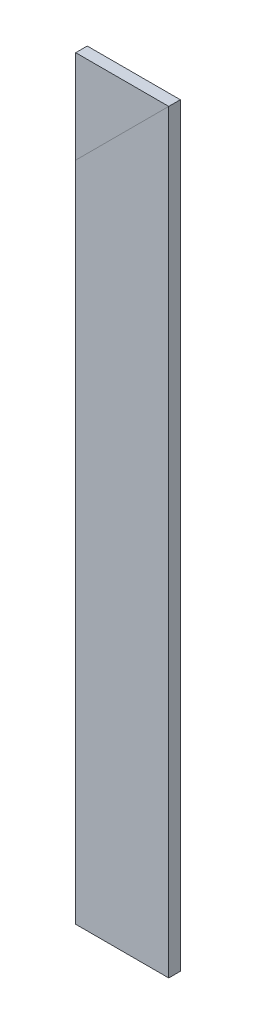
SolidWorks part; units mm, degrees
ref_plane "Alzado" through (0, 0, 0) normal (0, 0, 1) x (1, 0, 0)
ref_plane "Planta" through (0, 0, 0) normal (0, 1, 0) x (1, 0, 0)
ref_plane "Vista lateral" through (0, 0, 0) normal (1, 0, 0) x (0, 0, -1)
sketch "Croquis2" plane through (0, 0, 0) normal (1, 0, 0) x (0, 0, -1)
  line L1 (-3.155, 25.4) -> (3.155, 25.4)
  line L2 (-3.155, 25.4) -> (-3.155, -25.4)
  line L3 (-3.155, -25.4) -> (3.155, -25.4)
  line L4 (3.155, 25.4) -> (3.155, -25.4)
  line L5 (-3.155, 25.4) -> (3.155, -25.4) construction
  line L6 (-3.155, -25.4) -> (3.155, 25.4) construction
  point P0 (0, 0)
  dimension "D1" = 50.8
  dimension "D2" = 6.31
sketch3d "Croquis3D1"
  line L0 (0, 0, 0) -> (171, 0, 0)
  line L1 (171, 0, 0) -> (171, 0, -60)
  line L2 (171, 0, -60) -> (480, 0, -60)
  line L3 (480, 0, -60) -> (480, -386.69, -60)
  dimension "D1" = 171
  dimension "D2" = 60
  dimension "D3" = 309
  dimension "D4" = 386.69
sweep "Barrer1" add profiles "Croquis2" path "Croquis3D1"
sketch "Croquis3" plane through (0, -25.4, 0) normal (0, -1, 0) x (1, 0, 0)
  line L0 (0, 3.155) -> (0, -3.155)
  line L1 (0, 3.155) -> (0, -3.155) construction
  line L2 (0, 3.155) -> (0, -3.155) construction
  line L3 (0, -3.155) -> (174.155, -3.155)
  line L4 (174.155, 3.155) -> (174.155, -56.845) construction
  line L5 (174.155, -3.155) -> (174.155, 3.155)
  line L6 (174.155, 3.155) -> (0, 3.155)
extrude "Cortar-Extruir1" cut sketch "Croquis3" against normal blind 70
sketch "Croquis4" plane through (0, 0, -56.845) normal (0, 0, 1) x (1, 0, 0)
  line L0 (454.6, -386.69) -> (454.6, -335.89)
  line L1 (454.6, -25.4) -> (454.6, -386.69) construction
  line L2 (454.6, -335.89) -> (460.91, -335.89)
  line L3 (460.91, -335.89) -> (460.91, -386.69)
  line L4 (505.4, -386.69) -> (454.6, -386.69) construction
  line L5 (460.91, -386.69) -> (454.6, -386.69)
  dimension "D1" = 50.8
  dimension "D2" = 6.31
extrude "Saliente-Extruir1" add sketch "Croquis4" along normal blind 40
sketch "Croquis5" plane through (460.91, 0, 0) normal (1, 0, 0) x (0, 0, -1)
  line L0 (27.805, -378.6) -> (34.155, -378.6) construction
  line L1 (34.155, -346.6) -> (39.5306, -349.9802) construction
  circle A0 centre (34.155, -378.6) radius 6.35 construction
  circle A1 centre (34.155, -346.6) radius 6.35 construction
  circle A2 centre (34.155, -346.6) radius 6.35
  circle A3 centre (34.155, -378.6) radius 6.35
extrude "Cortar-Extruir2" cut sketch "Croquis5" against normal blind 10
sketch "Croquis6" plane through (167.845, 0, 0) normal (-1, 0, 0) x (0, 0, 1)
  line L0 (-3.155, 25.4) -> (-3.155, 19.09)
  line L1 (-3.155, 25.4) -> (-3.155, -25.4) construction
  line L2 (-3.155, 19.09) -> (-53.955, 19.09)
  line L3 (-53.955, 19.09) -> (-53.955, 25.4)
  line L4 (-3.155, 25.4) -> (-63.155, 25.4) construction
  line L5 (-53.955, 25.4) -> (-3.155, 25.4)
  dimension "D1" = 50.8
  dimension "D2" = 6.31
extrude "Saliente-Extruir2" add sketch "Croquis6" along normal blind 50.8
sketch "Croquis7" plane through (460.91, 0, 0) normal (1, 0, 0) x (0, 0, -1)
  line L0 (56.845, -335.89) -> (56.845, -386.69)
  line L1 (56.845, -386.69) -> (16.845, -386.69)
  line L2 (16.845, -386.69) -> (16.845, -335.89)
  line L3 (16.845, -335.89) -> (56.845, -335.89)
extrude "Cortar-Extruir3" cut sketch "Croquis7" against normal blind 10
sketch "Croquis9" plane through (0, 0, -63.155) normal (0, 0, -1) x (-1, 0, 0)
  line L0 (-454.6, -25.4) -> (-454.6, 25.4)
  line L1 (-167.845, 25.4) -> (-505.4, 25.4) construction
  line L2 (-454.6, 25.4) -> (-117.045, 25.4)
  line L3 (-117.045, 25.4) -> (-117.045, -25.4)
  line L4 (-117.045, -25.4) -> (-454.6, -25.4)
extrude "Cortar-Extruir4" cut sketch "Croquis9" against normal blind 67
